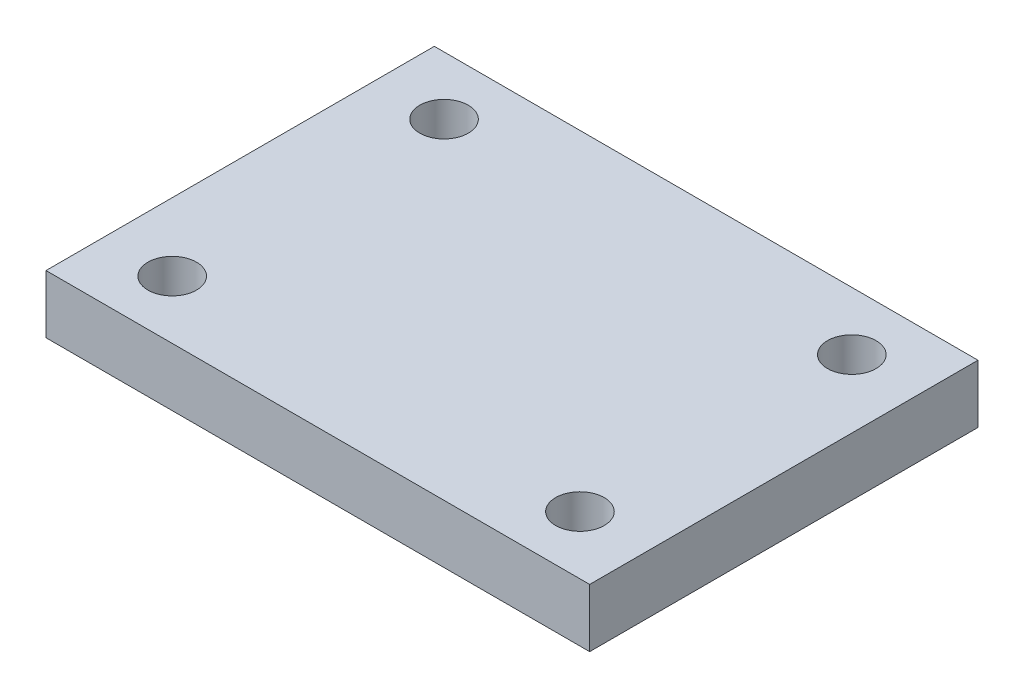
SolidWorks part; units mm, degrees
ref_plane "Front Plane" through (0, 0, 0) normal (0, 0, 1) x (1, 0, 0)
ref_plane "Top Plane" through (0, 0, 0) normal (0, 1, 0) x (1, 0, 0)
ref_plane "Right Plane" through (0, 0, 0) normal (1, 0, 0) x (0, 0, -1)
sketch "Sketch1" plane through (0, 0, 0) normal (0, 1, 0) x (1, 0, 0)
  line L1 (-14, 10) -> (14, 10)
  line L2 (-14, 10) -> (-14, -10)
  line L3 (-14, -10) -> (14, -10)
  line L4 (14, 10) -> (14, -10)
  line L5 (-14, 10) -> (14, -10) construction
  line L6 (-14, -10) -> (14, 10) construction
  point P0 (0, 0)
  dimension "D1" = 28
  dimension "D2" = 20
extrude "Boss-Extrude1" add sketch "Sketch1" along normal blind 3
sketch "Sketch2" plane through (0, 3, 0) normal (0, 1, 0) x (1, 0, 0)
  line L1 (-10.5, 7) -> (10.5, 7) construction
  line L2 (-10.5, 7) -> (-10.5, -7) construction
  line L3 (-10.5, -7) -> (10.5, -7) construction
  line L4 (10.5, 7) -> (10.5, -7) construction
  line L5 (-10.5, 7) -> (10.5, -7) construction
  line L6 (-10.5, -7) -> (10.5, 7) construction
  point P0 (0, 0)
  dimension "D1" = 21
  dimension "D2" = 14
sketch "Sketch5" plane through (0, 3, 0) normal (0, 1, 0) x (1, 0, 0)
  point P0 (-10.5, 7)
  point P3 (-10.5, -7)
  point P6 (10.5, -7)
  point P9 (10.5, 7)
hole_wizard "M3 Tapped Hole1" positions "Sketch5" profile "Sketch4" tap size "M3" standard "DIN" end condition through all
sketch "Sketch4" plane through (-10.5, 3, -7) normal (1, 0, 0) x (0, 0, 1)
  line L0 (0, 0) -> (0, 3)
  line L1 (0, 3) -> (1.25, 3)
  line L2 (1.25, 3) -> (1.25, 0)
  line L5 (1.25, 0) -> (0, 0)
  line L11 (0, -6.35) -> (0, 107.95) construction
  dimension "Thru Tap Drill Dia." = 2.5
  dimension "Thru Tap Drill Depth" = 3
cosmetic thread "Hole Thread1" parameters "D2"=3
cosmetic thread "Hole Thread2" parameters "D2"=3
cosmetic thread "Hole Thread3" parameters "D2"=3
cosmetic thread "Hole Thread4" parameters "D2"=3
